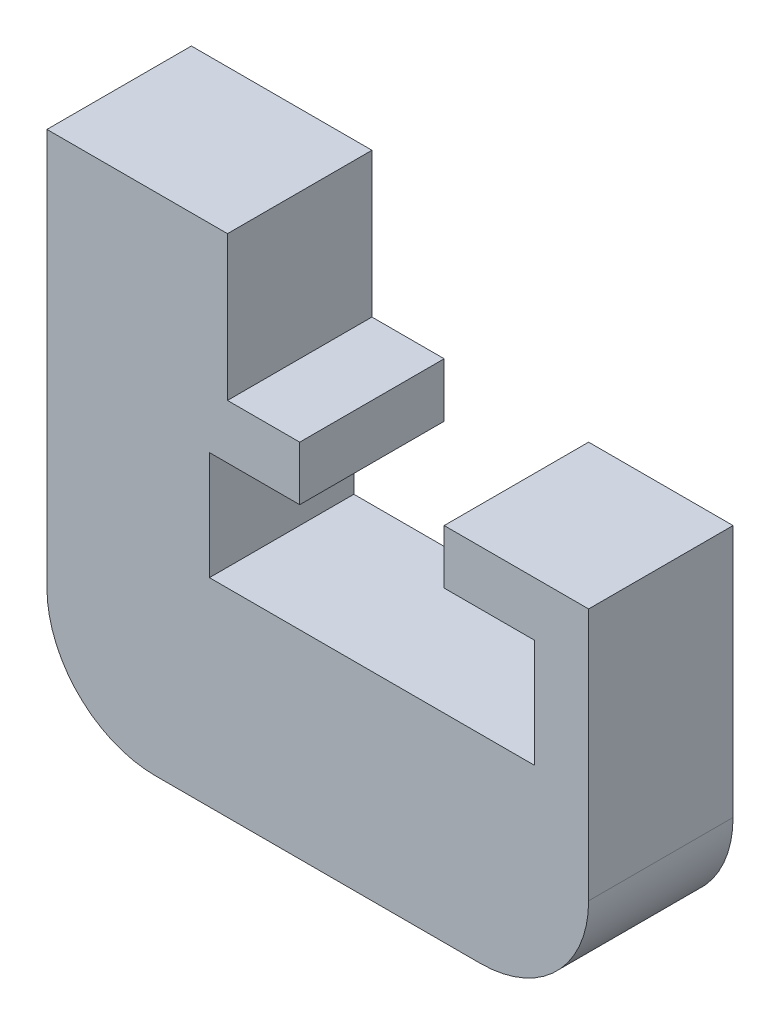
SolidWorks part; units mm, degrees
ref_plane "Alzado" through (0, 0, 0) normal (0, 0, 1) x (1, 0, 0)
ref_plane "Planta" through (0, 0, 0) normal (0, 1, 0) x (1, 0, 0)
ref_plane "Vista lateral" through (0, 0, 0) normal (1, 0, 0) x (0, 0, -1)
sketch "Croquis1" plane through (0, 0, 0) normal (0, 0, 1) x (1, 0, 0)
  line L0 (0, 23.001) -> (-5, 23.001)
  line L1 (-5, 23.001) -> (-5, 12.001)
  line L2 (6, 19.001) -> (10, 19.001)
  line L3 (10, 19.001) -> (10, 12.001)
  line L4 (6, 19.001) -> (6, 17.501)
  line L5 (6, 17.501) -> (8.5, 17.501)
  line L6 (8.5, 17.501) -> (8.5, 14.501)
  line L7 (8.5, 14.501) -> (-0.5, 14.501)
  line L8 (-0.5, 14.501) -> (-0.5, 17.501)
  line L9 (-0.5, 17.501) -> (2, 17.501)
  line L10 (2, 17.501) -> (2, 19.001)
  line L11 (2, 19.001) -> (0, 19.001)
  line L12 (0, 19.001) -> (0, 23.001)
  line L13 (7, 9.001) -> (-2, 9.001)
  arc A0 (-5, 12.001) -> (-2, 9.001) centre (-2, 12.001) ccw
  arc A1 (10, 12.001) -> (7, 9.001) centre (7, 12.001) cw
  dimension "D1" = 3
  dimension "D2" = 3
extrude "Saliente-Extruir1" add sketch "Croquis1" along normal blind 4
